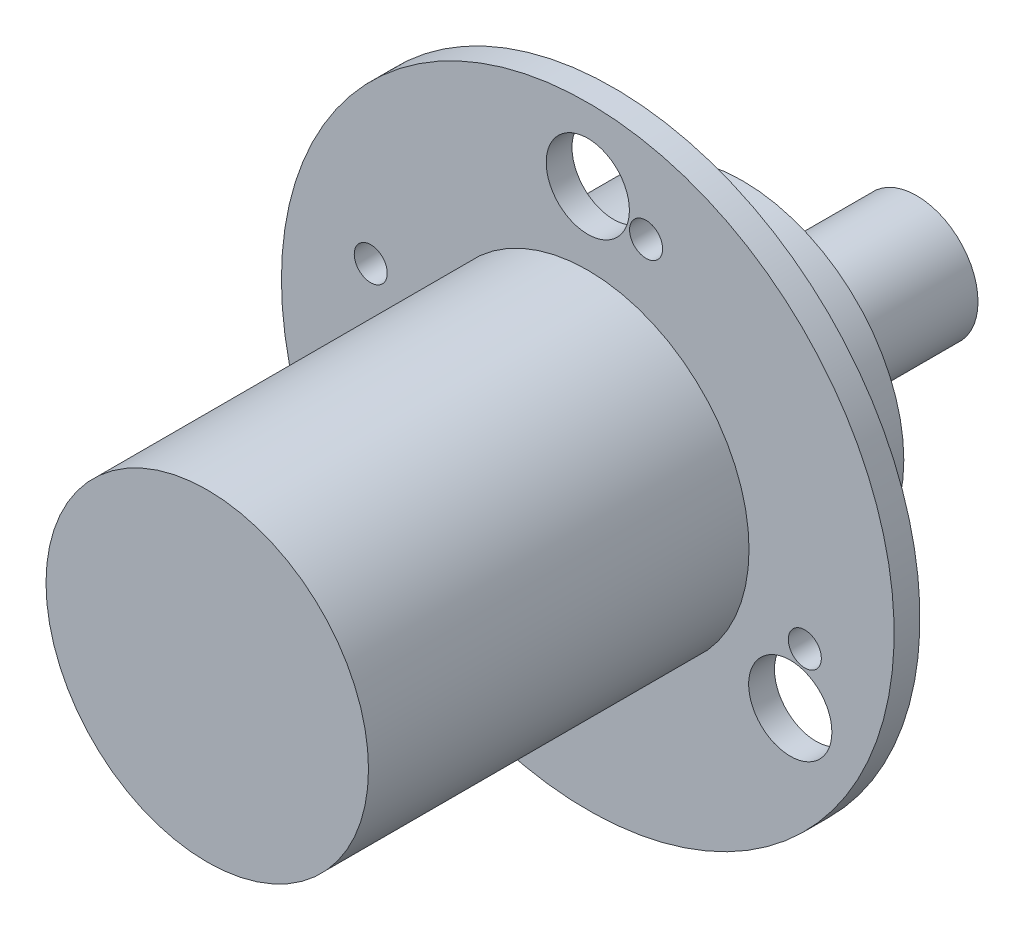
SolidWorks part; units mm, degrees
ref_plane "Front Plane" through (0, 0, 0) normal (0, 0, 1) x (1, 0, 0)
ref_plane "Top Plane" through (0, 0, 0) normal (0, 1, 0) x (1, 0, 0)
ref_plane "Right Plane" through (0, 0, 0) normal (1, 0, 0) x (0, 0, -1)
sketch "Sketch1" plane through (0, 0, 0) normal (0, 0, 1) x (1, 0, 0)
  circle A0 centre (0, 0) radius 6.35
  dimension "D1" = 12.7
extrude "Extrude1" add sketch "Sketch1" along normal blind 21.082
sketch "Sketch2" plane through (0, 0, 0) normal (0, 0, -1) x (-1, 0, 0)
  circle A0 centre (0, 0) radius 2.413
  dimension "D1" = 4.826
extrude "Extrude2" add sketch "Sketch2" along normal blind 6.858
ref_plane "Plane1" through (0, 0, 5.08) normal (0, 0, -1) x (-1, 0, 0)
sketch "Sketch3" plane through (0, 0, 5.08) normal (0, 0, -1) x (-1, 0, 0)
  circle A0 centre (0, 0) radius 12.065
  dimension "D1" = 24.13
extrude "Extrude3" add sketch "Sketch3" against normal blind 1.016
sketch "Sketch4" plane through (0, 0, 6.096) normal (0, 0, 1) x (1, 0, 0)
  line L0 (-0.6633, 0) -> (0, 0) construction
  line L1 (0, 0) -> (0, 15.7433) construction
  line L2 (0, 0) -> (7.9739, -4.6038) construction
  circle A0 centre (0, 9.2075) radius 1.6383
  circle A1 centre (7.9739, -4.6038) radius 1.6383
  circle A2 centre (-7.9739, -4.6037) radius 1.6383
  dimension "D2" = 3.2766
  dimension "D3" = 60
  dimension "D4" = 9.2075
  dimension "D1" = 9.2075
extrude "Cut-Extrude1" cut sketch "Sketch4" against normal through all
sketch "Sketch6" plane through (0, 0, 5.08) normal (0, 0, -1) x (-1, 0, 0)
  line L0 (0, 0) -> (-8.5767, 0.1446) construction
  line L1 (-9.0462, -0.6685) -> (-3.9442, 8.1685) construction
  line L2 (0, 0) -> (-8.5471, -2.2956) construction
  circle A0 centre (-8.5471, -2.2956) radius 0.65
  circle A1 centre (-2.2956, 8.5471) radius 0.65
  circle A2 centre (8.5471, 2.2956) radius 0.65
  dimension "D3" = 1.3
  dimension "D1" = 8.85
  dimension "D2" = 16
extrude "Cut-Extrude2" cut sketch "Sketch6" against normal through all
